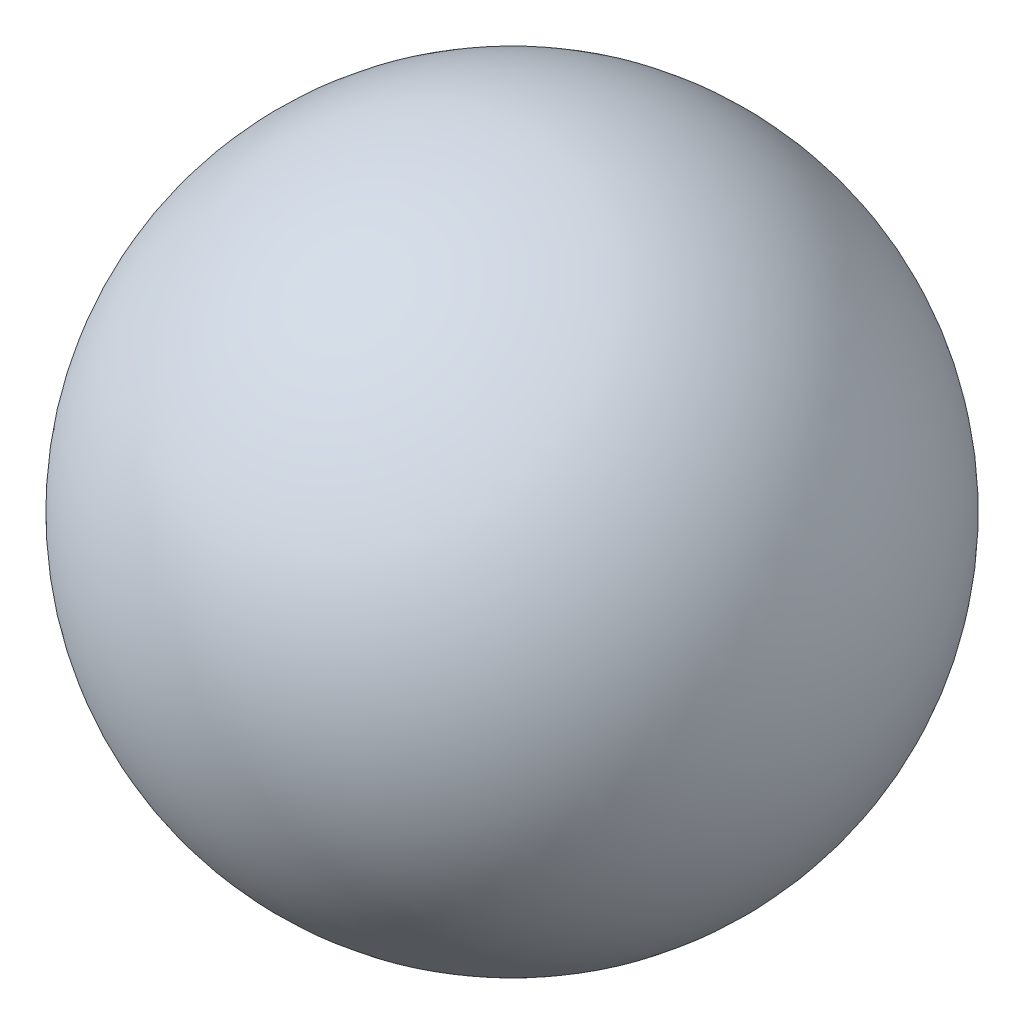
SolidWorks part; units mm, degrees
material "ABS"
ref_plane "Front Plane" through (0, 0, 0) normal (0, 0, 1) x (1, 0, 0)
ref_plane "Top Plane" through (0, 0, 0) normal (0, 1, 0) x (1, 0, 0)
ref_plane "Right Plane" through (0, 0, 0) normal (1, 0, 0) x (0, 0, -1)
sketch "Sketch1" plane through (0, 0, 0) normal (0, 0, 1) x (1, 0, 0)
  line L0 (0, 20) -> (0, -20) construction
  line L1 (0, 20) -> (0, 19)
  line L2 (0, -20) -> (0, -19)
  arc A0 (0, 20) -> (0, -20) centre (0, 0) ccw
  arc A1 (0, 19) -> (0, -19) centre (0, 0) ccw
  dimension "D2" = 40
  dimension "D1" = 1
revolve "Revolve1" add sketch "Sketch1" angle 360 about L0
